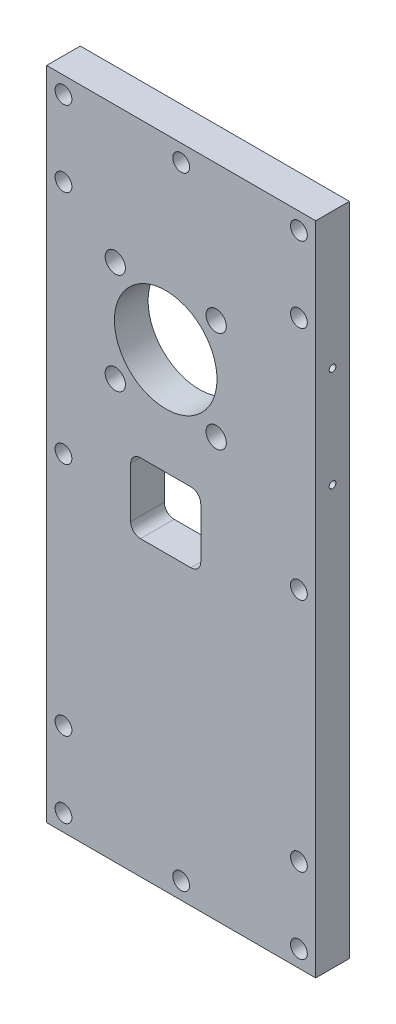
SolidWorks part; units mm, degrees
material "3.0205 (EN-AW 1200)"
ref_plane "Ebene vorne" through (0, 0, 0) normal (0, 0, 1) x (1, 0, 0)
ref_plane "Ebene oben" through (0, 0, 0) normal (0, 1, 0) x (1, 0, 0)
ref_plane "Ebene rechts" through (0, 0, 0) normal (1, 0, 0) x (0, 0, -1)
sketch "Skizze1" plane through (0, 0, 0) normal (0, 0, 1) x (1, 0, 0)
  line L1 (-69.0594, 70.0995) -> (10.9406, 70.0995)
  line L2 (-69.0594, 70.0995) -> (-69.0594, -124.9005)
  line L3 (-69.0594, -124.9005) -> (10.9406, -124.9005)
  line L4 (10.9406, 70.0995) -> (10.9406, -124.9005)
  dimension "D1" = 195
  dimension "D2" = 80
extrude "Aufsatz-Linear austragen1" add sketch "Skizze1" against normal blind 10
sketch "Skizze2" plane through (0, 0, -10) normal (0, 0, -1) x (-1, 0, 0)
  line L0 (69.0594, 70.0995) -> (69.0594, -124.9005) construction
  line L1 (33.6594, 14.5995) -> (33.6594, -27.4005) construction
  line L3 (33.6594, 14.5995) -> (69.0594, 14.5995) construction
  line L5 (18.6594, 29.5995) -> (48.6594, 29.5995) construction
  line L6 (48.6594, 29.5995) -> (48.6594, -0.4005) construction
  line L7 (48.6594, -0.4005) -> (18.6594, -0.4005) construction
  line L8 (18.6594, -0.4005) -> (18.6594, 29.5995) construction
  line L9 (18.6594, 29.5995) -> (48.6594, -0.4005) construction
  line L10 (69.0594, -27.4005) -> (-10.9406, -27.4005) construction
  line L11 (-10.9406, -124.9005) -> (-10.9406, 70.0995) construction
  line L12 (23.2413, -19.9005) -> (23.2413, -34.9005)
  line L13 (26.1594, -16.9824) -> (41.1594, -16.9824)
  line L14 (44.0774, -19.9005) -> (44.0774, -34.9005)
  line L15 (41.1594, -37.8185) -> (26.1594, -37.8185)
  line L16 (23.2413, -19.9005) -> (44.0774, -34.9005) construction
  line L17 (26.1594, -37.8185) -> (41.1594, -16.9824) construction
  circle A0 centre (18.6594, 29.5995) radius 3.015
  circle A1 centre (48.6594, 29.5995) radius 3.015
  circle A2 centre (18.6594, -0.4005) radius 3.015
  circle A3 centre (48.6594, -0.4005) radius 3.015
  circle A4 centre (33.6594, 14.5995) radius 15.25
  arc A5 (23.2413, -19.9005) -> (26.1594, -16.9824) centre (26.1594, -19.9005) cw
  arc A6 (41.1594, -16.9824) -> (44.0774, -19.9005) centre (41.1594, -19.9005) cw
  arc A7 (44.0774, -34.9005) -> (41.1594, -37.8185) centre (41.1594, -34.9005) cw
  arc A8 (26.1594, -37.8185) -> (23.2413, -34.9005) centre (26.1594, -34.9005) cw
  point P22 (33.6594, 14.5995)
  point P32 (33.6594, -27.4005)
  dimension "D1" = 30
  dimension "D3" = 6.03
  dimension "D2" = 30
  dimension "D4" = 35.4
  dimension "D5" = 42
  dimension "D6" = 15
extrude "Schnitt-Linear austragen1" cut sketch "Skizze2" against normal blind 10
sketch "Skizze3" plane through (0, 0, -10) normal (0, 0, -1) x (-1, 0, 0)
  line L0 (-5.9406, 65.0995) -> (63.8159, 65.0995) construction
  line L1 (63.8159, 65.0995) -> (63.8159, 42.5995) construction
  line L2 (63.8159, 42.5995) -> (63.8159, -27.4005) construction
  line L4 (63.8159, -27.4005) -> (63.8159, -97.4005) construction
  line L5 (63.8159, -97.4005) -> (63.8159, -119.9005) construction
  line L6 (63.8159, -119.9005) -> (-5.9406, -119.9005) construction
  line L7 (-5.9406, -119.9005) -> (-5.9406, -97.4005) construction
  line L8 (-5.9406, -97.4005) -> (-5.9406, -27.4005) construction
  line L10 (-5.9406, -27.4005) -> (-5.9406, 42.5995) construction
  line L11 (-5.9406, 42.5995) -> (-5.9406, 65.0995) construction
  line L12 (28.9377, 65.0995) -> (29.0594, 70.0995) construction
  line L13 (-10.9406, 70.0995) -> (69.0594, 70.0995) construction
  line L14 (28.9377, -119.9005) -> (29.0594, -124.9005) construction
  line L15 (69.0594, -124.9005) -> (-10.9406, -124.9005) construction
  line L16 (-10.9406, -124.9005) -> (-10.9406, 70.0995) construction
  circle A0 centre (-5.9406, 65.0995) radius 1.25
  circle A1 centre (63.8159, 65.0995) radius 1.25
  circle A2 centre (28.9377, 65.0995) radius 1.25
  circle A3 centre (63.8159, 42.5995) radius 1.25
  circle A5 centre (63.8159, -27.4005) radius 1.25
  circle A6 centre (63.8159, -97.4005) radius 1.25
  circle A7 centre (63.8159, -119.9005) radius 1.25
  circle A8 centre (28.9377, -119.9005) radius 1.25
  circle A9 centre (-5.9406, -119.9005) radius 1.25
  circle A10 centre (-5.9406, -97.4005) radius 1.25
  circle A11 centre (-5.9406, -27.4005) radius 1.25
  circle A13 centre (-5.9406, 42.5995) radius 1.25
  dimension "D4" = 2.5
  dimension "D1" = 5
  dimension "D2" = 5
  dimension "D3" = 5
  dimension "D5" = 70
extrude "Schnitt-Linear austragen2" cut sketch "Skizze3" against normal blind 5
sketch "Skizze4" plane through (0, 0, 0) normal (0, 0, 1) x (1, 0, 0)
  line L0 (-64.0594, 65.0995) -> (-64.0594, 42.5995) construction
  line L1 (-64.0594, 42.5995) -> (-64.0594, -27.4005) construction
  line L2 (-64.0594, -27.4005) -> (-64.0594, -97.4005) construction
  line L3 (-64.0594, -97.4005) -> (-64.0594, -119.9005) construction
  line L4 (5.9406, 65.0995) -> (5.9406, 42.5995) construction
  line L5 (5.9406, -119.9005) -> (-64.0594, -119.9005) construction
  line L6 (5.9406, 42.5995) -> (5.9406, -27.4005) construction
  line L7 (5.9406, -27.4005) -> (5.9406, -97.4005) construction
  line L8 (5.9406, -97.4005) -> (5.9406, -119.9005) construction
  line L11 (-64.0594, 65.0995) -> (5.9406, 65.0995) construction
  line L12 (-29.0594, 65.0995) -> (-29.0594, 70.0995) construction
  line L13 (10.9406, 70.0995) -> (-69.0594, 70.0995) construction
  line L15 (-69.0594, -124.9005) -> (10.9406, -124.9005) construction
  circle A0 centre (-64.0594, 65.0995) radius 2.5
  circle A1 centre (5.9406, 65.0995) radius 2.5
  circle A2 centre (5.9406, 42.5995) radius 2.5
  circle A3 centre (5.9406, -27.4005) radius 2.5
  circle A5 centre (5.9406, -97.4005) radius 2.5
  circle A6 centre (5.9406, -119.9005) radius 2.5
  circle A7 centre (-64.0594, -119.9005) radius 2.5
  circle A8 centre (-64.0594, -97.4005) radius 2.5
  circle A10 centre (-64.0594, -27.4005) radius 2.5
  circle A11 centre (-64.0594, 42.5995) radius 2.5
  circle A12 centre (-29.0594, -119.9005) radius 2.5
  circle A13 centre (-29.0594, 65.0995) radius 2.5
  dimension "D4" = 5
  dimension "D1" = 70
  dimension "D2" = 5
  dimension "D3" = 5
extrude "Schnitt-Linear austragen3" cut sketch "Skizze4" against normal blind 5
sketch "Skizze5" plane through (-69.0594, 0, 0) normal (-1, 0, 0) x (0, 0, 1)
  line L0 (0, 14.5995) -> (-10, 14.5995) construction
  line L1 (-5, 14.5995) -> (-5, -0.4005) construction
  line L2 (-5, 14.5995) -> (-5, 29.5995) construction
  line L3 (-10, 70.0995) -> (-10, -124.9005) construction
  line L4 (0, 70.0995) -> (0, -124.9005) construction
  line L5 (-10, 70.0995) -> (0, 70.0995) construction
  circle A0 centre (-5, 29.5995) radius 1
  circle A1 centre (-5, -0.4005) radius 1
  dimension "D1" = 2
  dimension "D2" = 30
  dimension "D3" = 55.5
extrude "Schnitt-Linear austragen4" cut sketch "Skizze5" against normal blind 20
sketch "Skizze6" plane through (10.9406, 0, 0) normal (1, 0, 0) x (0, 0, -1)
  line L0 (10, 14.5995) -> (0, 14.5995) construction
  line L1 (5, 14.5995) -> (5, -0.4005) construction
  line L2 (5, 14.5995) -> (5, 29.5995) construction
  line L3 (0, -124.9005) -> (0, 70.0995) construction
  line L4 (10, -124.9005) -> (10, 70.0995) construction
  line L5 (10, 70.0995) -> (0, 70.0995) construction
  circle A0 centre (5, 29.5995) radius 1
  circle A1 centre (5, -0.4005) radius 1
  dimension "D1" = 2
  dimension "D2" = 30
  dimension "D3" = 55.5
extrude "Schnitt-Linear austragen5" cut sketch "Skizze6" against normal blind 30
